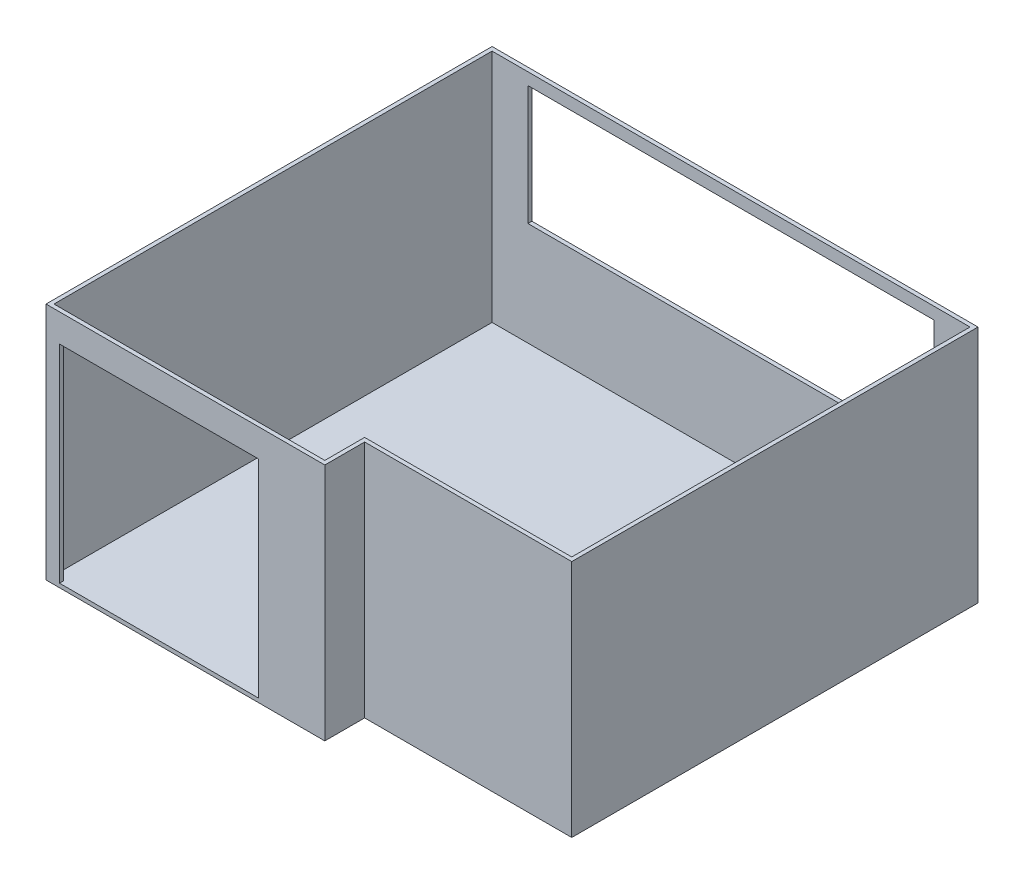
SolidWorks part; units mm, degrees
ref_plane "Front Plane" through (0, 0, 0) normal (0, 0, 1) x (1, 0, 0)
ref_plane "Top Plane" through (0, 0, 0) normal (0, 1, 0) x (1, 0, 0)
ref_plane "Right Plane" through (0, 0, 0) normal (1, 0, 0) x (0, 0, -1)
sketch "Sketch1" plane through (0, 0, 0) normal (0, 1, 0) x (1, 0, 0)
  line L1 (450, -2800) -> (-3050, -2800)
  line L2 (3050, -2300) -> (3050, 2800)
  line L3 (3050, 2800) -> (-3050, 2800)
  line L4 (-3050, -2800) -> (-3050, 2800)
  line L5 (2599.6877, -2386.5985) -> (-3050, 2800) construction
  line L6 (3050, 2800) -> (-3050, -2800) construction
  line L7 (3050, -2300) -> (450, -2300)
  line L10 (450, -2300) -> (450, -2800)
  line L11 (3050, -2300) -> (450, -2800) construction
  line L12 (1682.2233, -2563.034) -> (450, -2300) construction
  point P0 (0, 0)
  point P9 (1682.2233, -2563.034)
  dimension "D1" = 5600
  dimension "D2" = 6100
  dimension "D3" = 500
  dimension "D4" = 2600
extrude "Boss-Extrude1" add sketch "Sketch1" along normal blind 3000
shell "Shell2" thickness 50
sketch "Sketch2" plane through (0, 0, 2800) normal (0, 0, 1) x (1, 0, 0)
  line L0 (450, 3000) -> (450, 0) construction
  line L1 (-2880, 2650) -> (-380, 2650)
  line L2 (-2880, 2650) -> (-2880, 50)
  line L3 (-2880, 50) -> (-380, 50)
  line L4 (-380, 2650) -> (-380, 50)
  line L5 (-2880, 2650) -> (-380, 50) construction
  line L6 (-2880, 50) -> (-380, 2650) construction
  line L7 (-3050, 0) -> (450, 0) construction
  point P4 (-1630, 1350)
  dimension "D1" = 830
  dimension "D2" = 2500
  dimension "D3" = 50
  dimension "D4" = 2600
extrude "Cut-Extrude1" cut sketch "Sketch2" against normal blind 3000
sketch "Sketch3" plane through (0, 0, -2800) normal (0, 0, -1) x (-1, 0, 0)
  line L1 (0, 0) -> (0, 3221.1603) construction
  line L2 (-3050, 3000) -> (3050, 3000) construction
  line L3 (2550, 1350) -> (-2550, 1350)
  line L4 (2550, 1350) -> (2550, 2850)
  line L5 (2550, 2850) -> (-2550, 2850)
  line L6 (-2550, 1350) -> (-2550, 2850)
  line L7 (2550, 1350) -> (-2550, 2850) construction
  line L8 (2550, 2850) -> (-2550, 1350) construction
  point P0 (0, 2100)
  dimension "D1" = 5100
  dimension "D2" = 1500
  dimension "D3" = 150
extrude "Cut-Extrude2" cut sketch "Sketch3" against normal blind 3000
